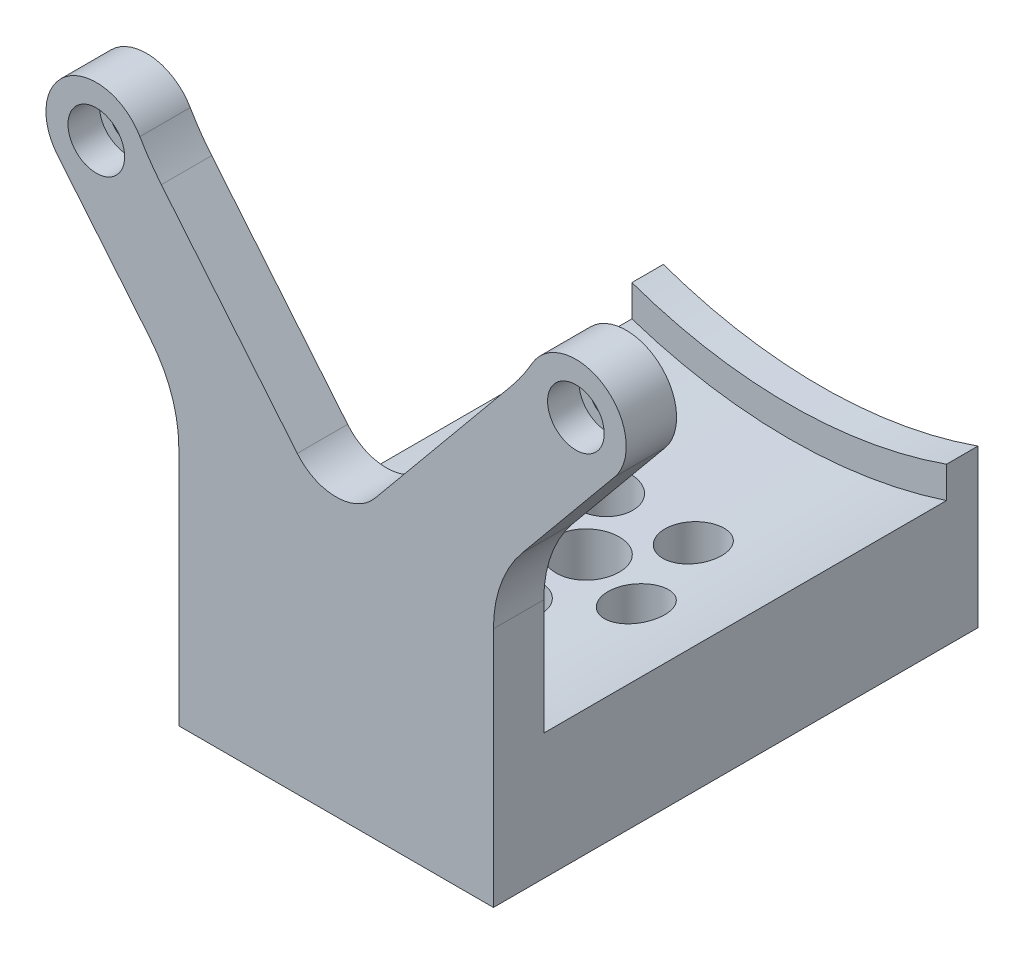
SolidWorks part; units mm, degrees
ref_plane "Front Plane" through (0, 0, 0) normal (0, 0, 1) x (1, 0, 0)
ref_plane "Top Plane" through (0, 0, 0) normal (0, 1, 0) x (1, 0, 0)
ref_plane "Right Plane" through (0, 0, 0) normal (1, 0, 0) x (0, 0, -1)
sketch "Sketch3" plane through (0, 0, 0) normal (0, 0, 1) x (1, 0, 0)
  line L0 (0, 0) -> (50, 0)
  line L1 (0, 0) -> (0, 20)
  line L2 (50, 0) -> (50, 20)
  arc A0 (0, 20) -> (50, 20) centre (25, 95.9934) ccw
  point P9 (25, 0)
  dimension "D2" = 80
  dimension "D1" = 50
  dimension "D3" = 20
extrude "Boss-Extrude1" add sketch "Sketch3" along normal blind 64
sketch "Sketch4" plane through (0, 0, 0) normal (0, 0, -1) x (-1, 0, 0)
  line L0 (-50, 0) -> (0, 0)
  line L1 (0, 0) -> (0, 25)
  line L3 (-50, 0) -> (-50, 25)
  arc A0 (-50, 25) -> (0, 25) centre (-25, 95.9934) ccw
  dimension "D1" = 25
extrude "Boss-Extrude2" add sketch "Sketch4" along normal blind 5
sketch "Sketch5" plane through (0, 0, 64) normal (0, 0, 1) x (1, 0, 0)
  line L0 (25, 95.9934) -> (25, 51.9934) construction
  line L1 (25, 95.9934) -> (-13.1051, 73.9934) construction
  line L2 (25, 95.9934) -> (63.1051, 73.9934) construction
  line L3 (0, 0) -> (50, 0)
  line L4 (0, 0) -> (0, 45.5362)
  line L5 (50, 0) -> (50, 45.5362)
  line L6 (-19.2762, 68.9025) -> (0, 45.5362)
  line L7 (69.2762, 68.9025) -> (50, 45.5362)
  line L8 (-2.77, 73.0843) -> (18.8289, 46.9025)
  line L9 (31.1711, 46.9025) -> (52.77, 73.0843)
  circle A0 centre (25, 95.9934) radius 44 construction
  circle A1 centre (63.1051, 73.9934) radius 2.75
  circle A2 centre (-13.1051, 73.9934) radius 2.75
  circle A3 centre (25, 95.9934) radius 36 construction
  arc A4 (69.2762, 68.9025) -> (56.1769, 77.9934) centre (63.1051, 73.9934) ccw
  arc A5 (-6.1769, 77.9934) -> (-19.2762, 68.9025) centre (-13.1051, 73.9934) ccw
  circle A6 centre (25, 51.9934) radius 2.75 construction
  circle A7 centre (25, 51.9934) radius 8 construction
  arc A8 (-6.1769, 77.9934) -> (-2.77, 73.0843) centre (25, 95.9934) ccw
  arc A9 (52.77, 73.0843) -> (56.1769, 77.9934) centre (25, 95.9934) ccw
  arc A10 (18.8289, 46.9025) -> (31.1711, 46.9025) centre (25, 51.9934) ccw
  dimension "D1" = 88
  dimension "D2" = 5.5
  dimension "D5" = 72
  dimension "D6" = 16
  dimension "D3" = 60
  dimension "D4" = 60
extrude "Boss-Extrude3" add sketch "Sketch5" along normal blind 8
sketch "Sketch6" plane through (0, 0, 72) normal (0, 0, 1) x (1, 0, 0)
  circle A0 centre (-13.1051, 73.9934) radius 4.5
  circle A1 centre (63.1051, 73.9934) radius 4.5
  dimension "D1" = 9
extrude "Cut-Extrude1" cut sketch "Sketch6" against normal blind 5
sketch "Sketch7" plane through (0, 0, 0) normal (0, -1, 0) x (1, 0, 0)
  line L0 (0, 72) -> (50, 72) construction
  line L1 (0, 64) -> (0, 0) construction
  circle A0 centre (25, 32) radius 12 construction
  circle A1 centre (25, 44) radius 2.75
  circle A2 centre (36.4127, 35.7082) radius 2.75
  circle A3 centre (32.0534, 22.2918) radius 2.75
  circle A4 centre (17.9466, 22.2918) radius 2.75
  circle A5 centre (13.5873, 35.7082) radius 2.75
  circle A6 centre (25, 32) radius 5
  point P5 (25, 72)
  point P8 (0, 32)
  dimension "D1" = 24
  dimension "D2" = 5.5
  dimension "D4" = 10
  dimension "D3" = 5
extrude "Cut-Extrude2" cut sketch "Sketch7" against normal through all
ref_plane "Plane1" through (0, 20, 0) normal (0, 1, 0) x (1, 0, 0)
sketch "Sketch8" plane through (0, 20, 0) normal (0, 1, 0) x (1, 0, 0)
  circle A0 centre (25, -44) radius 4.5
  circle A1 centre (17.9466, -22.2918) radius 4.5
  circle A2 centre (32.0534, -22.2918) radius 4.5
  circle A3 centre (36.4127, -35.7082) radius 4.5
  circle A4 centre (13.5873, -35.7082) radius 4.5
  dimension "D1" = 9
extrude "Cut-Extrude3" cut sketch "Sketch8" against normal offset from surface (14 mm away) 6 up to face at (25, 0, 41.25)
fillet "Fillet2" radius 20 2 edges at (50, 45.5362, 68) (0, 45.5362, 68)
